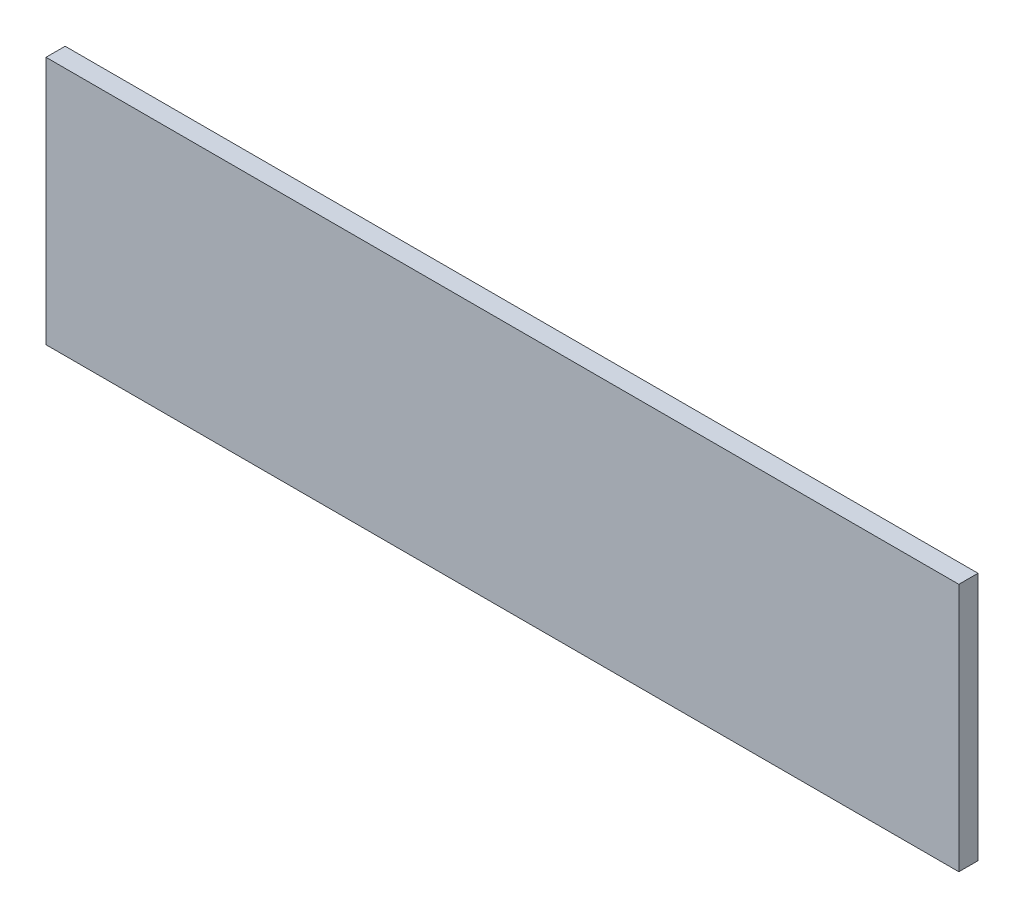
SolidWorks part; units mm, degrees
ref_plane "Front" through (0, 0, 0) normal (0, 0, 1) x (1, 0, 0)
ref_plane "Top" through (0, 0, 0) normal (0, 1, 0) x (1, 0, 0)
ref_plane "Right" through (0, 0, 0) normal (1, 0, 0) x (0, 0, -1)
sketch "Sketch1" plane through (0, 0, 0) normal (0, 0, 1) x (1, 0, 0)
  line L1 (-143, -39) -> (143, -39)
  line L2 (-143, -39) -> (-143, 39)
  line L3 (-143, 39) -> (143, 39)
  line L4 (143, -39) -> (143, 39)
  line L5 (-143, -39) -> (143, 39) construction
  line L6 (-143, 39) -> (143, -39) construction
  point P0 (0, 0)
  dimension "D1" = 78
  dimension "D2" = 286
extrude "Boss-Extrude1" add sketch "Sketch1" along normal blind 6
